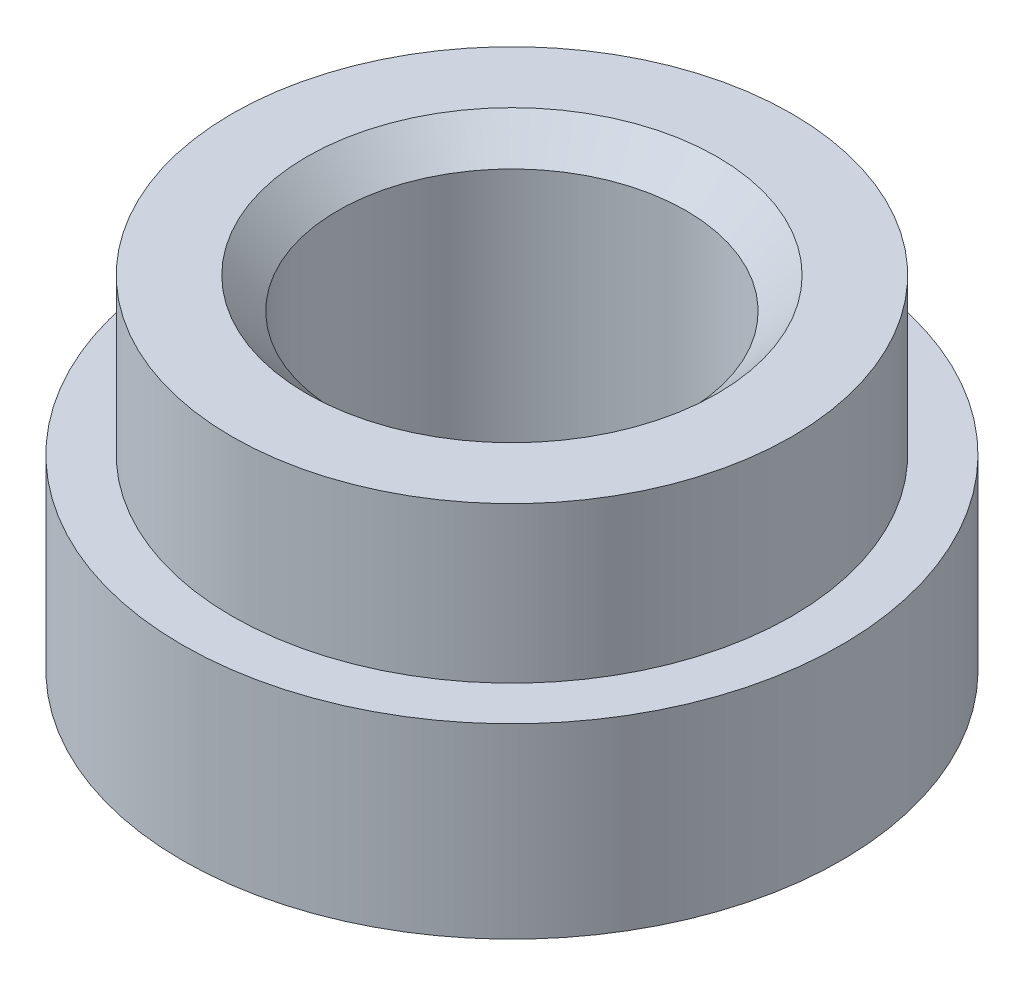
SolidWorks part; units mm, degrees
material "AISI 316 Annealed Stainless Steel Bar (SS)"
ref_plane "Front Plane" through (0, 0, 0) normal (0, 0, 1) x (1, 0, 0)
ref_plane "Top Plane" through (0, 0, 0) normal (0, 1, 0) x (1, 0, 0)
ref_plane "Right Plane" through (0, 0, 0) normal (1, 0, 0) x (0, 0, -1)
sketch "Sketch1" plane through (0, 0, 0) normal (0, 1, 0) x (1, 0, 0)
  circle A0 centre (0, 0) radius 2.65
  dimension "D1" = 5.3
extrude "Boss-Extrude1" add sketch "Sketch1" along normal blind 1.5
sketch "Sketch2" plane through (0, 1.5, 0) normal (0, 1, 0) x (1, 0, 0)
  circle A0 centre (0, 0) radius 2.25
  dimension "D1" = 4.5
extrude "Boss-Extrude2" add sketch "Sketch2" along normal blind 1.25
sketch "Sketch3" plane through (0, 2.75, 0) normal (0, 1, 0) x (1, 0, 0)
  circle A0 centre (0, 0) radius 1.4
  dimension "D1" = 2.8
extrude "Cut-Extrude1" cut sketch "Sketch3" against normal through all
chamfer "Chamfer1" distance 0.25 angle 45 2 edges at (0, 2.75, 1.4) (0, 0, 1.4)
